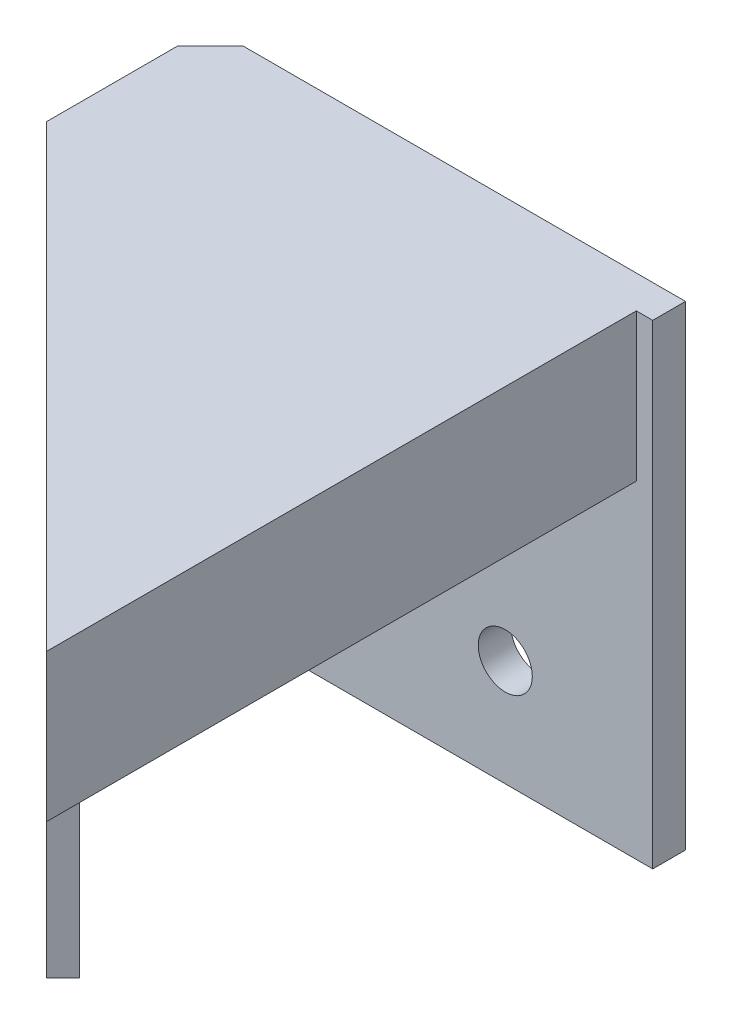
SolidWorks part; units mm, degrees
ref_plane "Front Plane" through (0, 0, 0) normal (0, 0, 1) x (1, 0, 0)
ref_plane "Top Plane" through (0, 0, 0) normal (0, 1, 0) x (1, 0, 0)
ref_plane "Right Plane" through (0, 0, 0) normal (1, 0, 0) x (0, 0, -1)
sketch "Sketch1" plane through (0, 0, 0) normal (0, 0, 1) x (1, 0, 0)
  line L1 (10.2499, -35.45) -> (-16.7501, -35.45)
  line L2 (10.2499, -35.45) -> (10.2499, -6.45)
  line L3 (10.2499, -6.45) -> (-16.7501, -6.45)
  line L4 (-16.7501, -35.45) -> (-16.7501, -6.45)
  point P0 (0, 0)
  point P9 (0, 0)
  dimension "D2" = 27
  dimension "D1" = 29
extrude "Boss-Extrude1" add sketch "Sketch1" along normal blind 2
sketch "Sketch4" plane through (-16.7501, 0, 0) normal (-1, 0, 0) x (0, 0, 1)
  line L0 (2, -35.45) -> (0, -35.45) construction
  line L1 (0, -6.45) -> (10, -6.45)
  line L2 (0, -6.45) -> (0, -35.45)
  line L3 (0, -35.45) -> (10, -35.45)
  line L4 (10, -6.45) -> (10, -35.45)
  dimension "D1" = 10
extrude "Boss-Extrude3" add sketch "Sketch4" along normal blind 2
sketch "Sketch5" plane through (0, -35.45, 0) normal (0, -1, 0) x (1, 0, 0)
  line L0 (-18.7501, 10) -> (-2.4866, 26.2635)
  line L1 (-2.4866, 26.2635) -> (-1.4866, 25.2635)
  line L2 (-1.4866, 25.2635) -> (-16.7501, 10)
  line L3 (-16.7501, 2) -> (-16.7501, 10) construction
  line L4 (-16.7501, 10) -> (-18.7501, 10)
  dimension "D1" = 135
  dimension "D2" = 23
extrude "Boss-Extrude4" add sketch "Sketch5" against normal up to surface (29 mm away) up to face at (-8.4167, -6.45, 4)
sketch "Sketch6" plane through (-13.375, 0, 13.375) normal (0.7071, 0, -0.7071) x (-0.7071, 0, -0.7071)
  line L0 (-16.8128, -6.45) -> (-16.8128, -35.45) construction
  line L2 (4.773, -35.45) -> (-16.8128, -35.45) construction
  line L3 (-11.8128, -32.45) -> (-11.8128, -18.45) construction
  circle A1 centre (-11.8128, -32.45) radius 1.65
  circle A2 centre (-11.8128, -18.45) radius 1.65
  dimension "D1" = 14
  dimension "D4" = 5
  dimension "D5" = 3
  dimension "D6" = 3.3
extrude "Cut-Extrude1" cut sketch "Sketch6" against normal blind 2
chamfer "Chamfer1" distance 1 angle 45 1 edges at (-16.7501, -20.95, 2)
sketch "Sketch7" plane through (0, 0, 2) normal (0, 0, 1) x (1, 0, 0)
  line L0 (-18.7501, -6.45) -> (-2.4866, -6.45) construction
  line L1 (-14.7501, -14.45) -> (8.2499, -14.45)
  line L2 (-14.7501, -14.45) -> (-14.7501, -7.45)
  line L3 (-14.7501, -7.45) -> (8.2499, -7.45)
  line L4 (8.2499, -14.45) -> (8.2499, -7.45)
  line L5 (-14.7501, -14.45) -> (8.2499, -7.45) construction
  line L6 (-14.7501, -7.45) -> (8.2499, -14.45) construction
  line L14 (10.2499, -35.45) -> (10.2499, -6.45) construction
  line L15 (-18.7501, -6.45) -> (-18.7501, -35.45) construction
  point P0 (-3.2501, -10.95)
  point P5 (-3.2501, -10.95)
  point P6 (0, 0)
  dimension "D1" = 4
  dimension "D2" = 7
  dimension "D3" = 1
  dimension "D4" = 2
extrude "Cut-Extrude3" cut sketch "Sketch7" against normal up to surface (2 mm away) and the other way up to surface up to face at (-4.2501, -20.95, 0) other way up to face at (-4.8554, -18.45, 23.8946)
sketch "Sketch9" plane through (0, 0, 0) normal (0, 0, -1) x (-1, 0, 0)
  line L0 (-10.2499, -20.95) -> (18.7501, -20.95) construction
  line L1 (-9.2499, -15.45) -> (18.7501, -15.45)
  line L2 (-9.2499, -15.45) -> (-9.2499, -6.45)
  line L3 (-9.2499, -6.45) -> (18.7501, -6.45)
  line L4 (18.7501, -15.45) -> (18.7501, -6.45)
  line L5 (-10.2499, -35.45) -> (-10.2499, -6.45) construction
  line L6 (-8.2499, -14.45) -> (14.7501, -14.45) construction
  line L9 (14.7501, -7.45) -> (-8.2499, -7.45) construction
  line L10 (-8.2499, -7.45) -> (-8.2499, -14.45) construction
  line L11 (-8.2499, -14.45) -> (14.7501, -14.45)
  line L12 (-8.2499, -14.45) -> (-8.2499, -7.45)
  line L13 (-8.2499, -7.45) -> (14.7501, -7.45)
  line L14 (14.7501, -14.45) -> (14.7501, -7.45)
  line L15 (-8.2499, -14.45) -> (14.7501, -7.45) construction
  line L16 (-8.2499, -7.45) -> (14.7501, -14.45) construction
  line L17 (18.7501, -6.45) -> (18.7501, -35.45) construction
  point P0 (12.425, 0)
  point P13 (3.2501, -10.95)
  point P23 (0, 0)
  dimension "D1" = 1
  dimension "D2" = 1
  dimension "D4" = 1
extrude "Boss-Extrude6" add sketch "Sketch9" against normal up to surface (38 mm away)
chamfer "Chamfer3" distance 2 angle 45 1 edges at (-18.7501, -20.95, 0)
sketch "Sketch10" plane through (0, 0, 2) normal (0, 0, 1) x (1, 0, 0)
  line L0 (10.2499, -35.45) -> (-15.7501, -35.45) construction
  line L1 (10.2499, -35.45) -> (10.2499, -6.45) construction
  circle A0 centre (1.2499, -28.95) radius 1.65
  dimension "D1" = 6.5
  dimension "D2" = 9
  dimension "D3" = 3.3
extrude "Cut-Extrude4" cut sketch "Sketch10" against normal blind 10
sketch "Sketch11" plane through (0, 0, 0) normal (0, 0, -1) x (-1, 0, 0)
  line L0 (-8.2499, -14.45) -> (14.7501, -14.45) construction
  line L1 (-6.1499, -14.45) -> (-3.3499, -14.45)
  line L2 (-6.1499, -14.45) -> (-6.1499, -17.35)
  line L3 (-6.1499, -17.35) -> (-3.3499, -17.35)
  line L4 (-3.3499, -14.45) -> (-3.3499, -17.35)
  line L5 (-10.2499, -35.45) -> (-10.2499, -6.45) construction
  line L6 (9.8501, -14.45) -> (12.6501, -14.45)
  line L7 (9.8501, -14.45) -> (9.8501, -17.35)
  line L8 (9.8501, -17.35) -> (12.6501, -17.35)
  line L9 (12.6501, -14.45) -> (12.6501, -17.35)
  line L10 (16.7501, -35.45) -> (16.7501, -6.45) construction
  dimension "D1" = 2.8
  dimension "D2" = 2.9
  dimension "D3" = 4.1
  dimension "D4" = 4.1
  dimension "D5" = 2.8
  dimension "D6" = 2.9
extrude "Boss-Extrude7" add sketch "Sketch11" along normal blind 3
